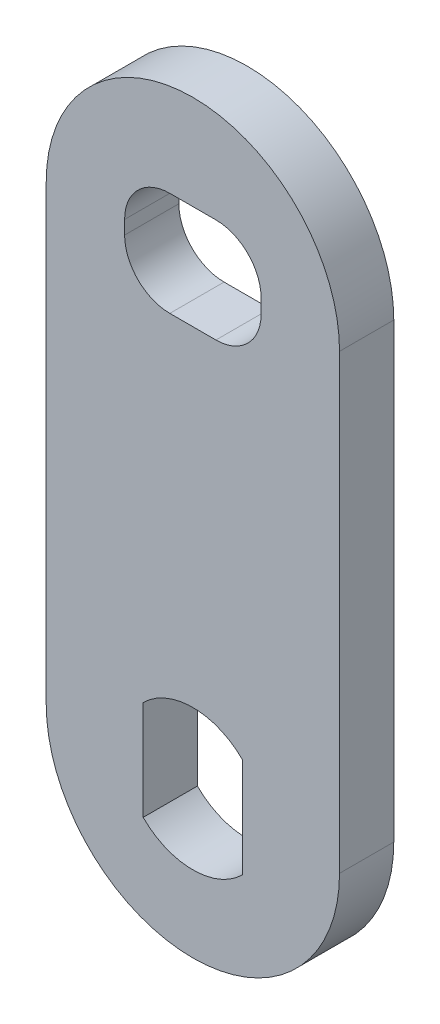
SolidWorks part; units mm, degrees
ref_plane "Front Plane" through (0, 0, 0) normal (0, 0, 1) x (1, 0, 0)
ref_plane "Top Plane" through (0, 0, 0) normal (0, 1, 0) x (1, 0, 0)
ref_plane "Right Plane" through (0, 0, 0) normal (1, 0, 0) x (0, 0, -1)
sketch "Sketch1" plane through (0, 0, 0) normal (0, 0, 1) x (1, 0, 0)
  line L1 (-3.775, 15.375) -> (3.775, 15.375)
  line L2 (-8.11, 12.5) -> (-8.11, -12.5)
  line L3 (-3.775, 15.375) -> (-3.775, 9.625)
  line L4 (8.11, 12.5) -> (8.11, -12.5)
  line L5 (-8.11, 12.5) -> (8.11, -12.5) construction
  line L6 (-8.11, -12.5) -> (8.11, 12.5) construction
  line L7 (-3.775, 9.625) -> (3.775, 9.625)
  line L8 (3.775, 15.375) -> (3.775, 9.625)
  line L9 (-3.775, 15.375) -> (3.775, 9.625) construction
  line L10 (-3.775, 9.625) -> (3.775, 15.375) construction
  arc A0 (8.11, 12.5) -> (-8.11, 12.5) centre (0, 12.5) ccw
  arc A1 (-8.11, -12.5) -> (8.11, -12.5) centre (0, -12.5) ccw
  point P0 (0, 0)
  dimension "D3" = 8.11
  dimension "D4" = 8.11
  dimension "D1" = 16.22
  dimension "D2" = 25
  dimension "D5" = 25
  dimension "D6" = 7.55
  dimension "D7" = 5.75
extrude "Boss-Extrude1" add sketch "Sketch1" along normal blind 3
fillet "Fillet1" radius 2.5 4 edges at (3.775, 9.625, 1.5) (3.775, 15.375, 1.5) (-3.775, 9.625, 1.5) (-3.775, 15.375, 1.5)
sketch "Sketch2" plane through (0, 0, 3) normal (0, 0, 1) x (1, 0, 0)
  line L0 (0, 0) -> (0, -29.2237) construction
  line L3 (-2.75, -9.75) -> (-2.75, -15.25)
  line L5 (2.75, -9.75) -> (2.75, -15.25)
  line L6 (-2.75, -9.75) -> (2.75, -15.25) construction
  line L7 (-2.75, -15.25) -> (2.75, -9.75) construction
  arc A0 (2.75, -9.75) -> (-2.75, -9.75) centre (0, -12.5) ccw
  arc A1 (-2.75, -15.25) -> (2.75, -15.25) centre (0, -12.5) ccw
  point P0 (0, -12.5)
  dimension "D1" = 5.5
  dimension "D2" = 5.5
extrude "Cut-Extrude1" cut sketch "Sketch2" against normal blind 3
